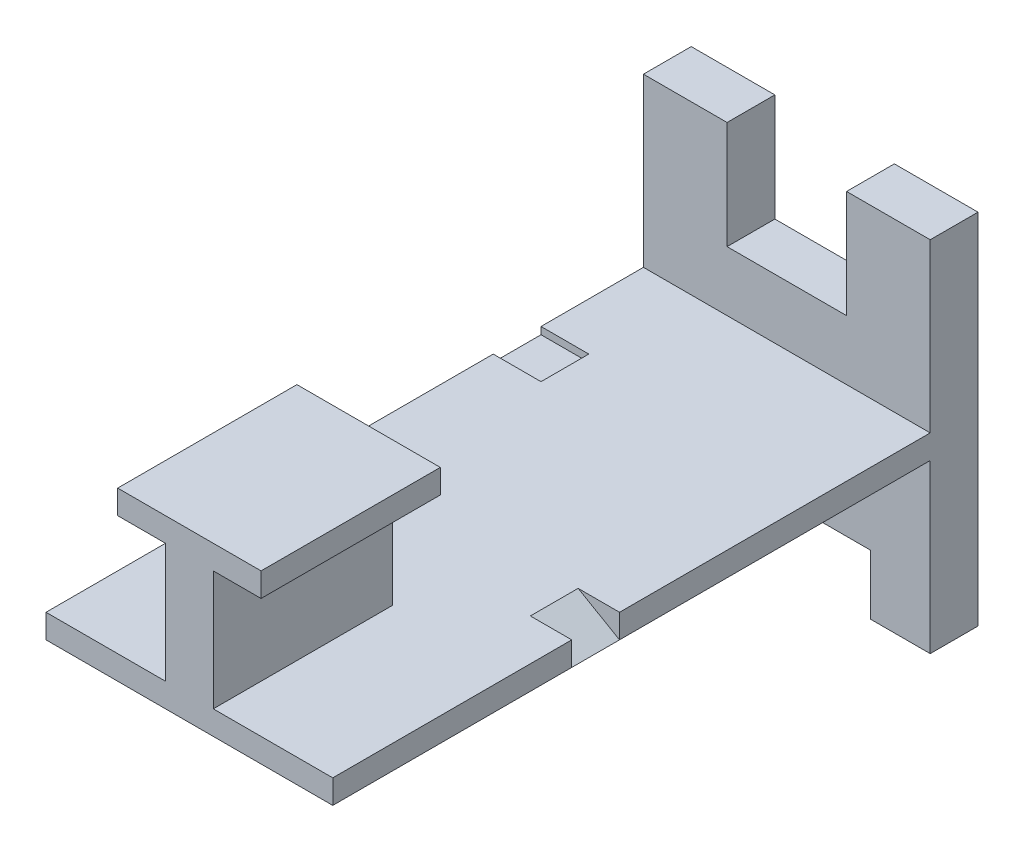
SolidWorks part; units mm, degrees
ref_plane "Спереди" through (0, 0, 0) normal (0, 0, 1) x (1, 0, 0)
ref_plane "Сверху" through (0, 0, 0) normal (0, 1, 0) x (1, 0, 0)
ref_plane "Справа" through (0, 0, 0) normal (1, 0, 0) x (0, 0, -1)
sketch "Эскиз1" plane through (0, 0, 0) normal (0, 0, 1) x (1, 0, 0)
  line L5 (0, 0) -> (120, 0)
  line L6 (0, 0) -> (0, -150)
  line L7 (0, -150) -> (120, -150)
  line L8 (120, 0) -> (120, -150)
  dimension "D1" = 150
  dimension "D2" = 120
extrude "Бобышка-Вытянуть1" add sketch "Эскиз1" along normal blind 20
sketch "Эскиз2" plane through (0, 0, 20) normal (0, 0, 1) x (1, 0, 0)
  line L6 (0, -75) -> (120, -75) construction
  line L7 (0, 0) -> (0, -150) construction
  line L8 (120, -150) -> (120, 0) construction
  line L9 (0, -80) -> (0, -70)
  line L10 (0, -70) -> (120, -70)
  line L11 (120, -70) -> (120, -80)
  line L12 (120, -80) -> (0, -80)
  point P9 (0, -75)
  dimension "D1" = 10
extrude "Бобышка-Вытянуть3" add sketch "Эскиз2" along normal blind 250
sketch "Эскиз3" plane through (0, 0, 20) normal (0, 0, 1) x (1, 0, 0)
  line L0 (120, 0) -> (0, 0) construction
  line L1 (35, 0) -> (85, 0)
  line L2 (35, 0) -> (35, -45)
  line L3 (35, -45) -> (85, -45)
  line L4 (85, 0) -> (85, -45)
  dimension "D1" = 35
  dimension "D2" = 35
  dimension "D3" = 45
extrude "Вырез-Вытянуть1" cut sketch "Эскиз3" against normal through all
sketch "Эскиз4" plane through (0, 0, 20) normal (0, 0, 1) x (1, 0, 0)
  line L0 (0, -150) -> (120, -150) construction
  line L1 (25, -150) -> (95, -150)
  line L2 (25, -150) -> (25, -125)
  line L3 (25, -125) -> (95, -125)
  line L4 (95, -150) -> (95, -125)
  dimension "D1" = 25
  dimension "D2" = 25
  dimension "D3" = 25
extrude "Вырез-Вытянуть2" cut sketch "Эскиз4" against normal through all
sketch "Эскиз5" plane through (0, -70, 0) normal (0, 1, 0) x (1, 0, 0)
  line L0 (0, -270) -> (0, -20) construction
  line L1 (0, -62.8599) -> (20, -62.8599)
  line L2 (0, -62.8599) -> (0, -82.8599)
  line L3 (0, -82.8599) -> (20, -82.8599)
  line L4 (20, -62.8599) -> (20, -82.8599)
  dimension "D1" = 20
  dimension "D2" = 20
extrude "Вырез-Вытянуть3" cut sketch "Эскиз5" against normal blind 3
sketch "Эскиз6" plane through (0, 0, 270) normal (0, 0, 1) x (1, 0, 0)
  line L0 (120, -80) -> (102.6795, -70)
  line L1 (120, -70) -> (0, -70) construction
  line L2 (102.6795, -70) -> (120, -70)
  line L3 (120, -80) -> (120, -70) construction
  line L4 (120, -70) -> (120, -80)
  dimension "D1" = 30
  dimension "D2" = 17.3205
extrude "Вырез-Вытянуть6" cut sketch "Эскиз6" against normal blind 20 from offset 100 contours L4 L0 L2 offset against normal yes
sketch "Эскиз7" plane through (0, -70, 0) normal (0, 1, 0) x (1, 0, 0)
  line L0 (120, -270) -> (0, -270) construction
  line L1 (50, -270) -> (70, -270)
  line L2 (50, -270) -> (50, -195)
  line L3 (50, -195) -> (70, -195)
  line L4 (70, -270) -> (70, -195)
  line L5 (0, -270) -> (0, -82.8599) construction
  dimension "D1" = 50
  dimension "D2" = 50
  dimension "D3" = 75
extrude "Бобышка-Вытянуть4" add sketch "Эскиз7" along normal blind 50
sketch "Эскиз8" plane through (0, -20, 0) normal (0, 1, 0) x (1, 0, 0)
  line L0 (120, -270) -> (70, -270) construction
  line L1 (30, -195) -> (90, -195)
  line L2 (30, -195) -> (30, -270)
  line L3 (30, -270) -> (90, -270)
  line L4 (90, -195) -> (90, -270)
  dimension "D1" = 75
  dimension "D2" = 20
  dimension "D3" = 20
extrude "Бобышка-Вытянуть5" add sketch "Эскиз8" along normal blind 10
